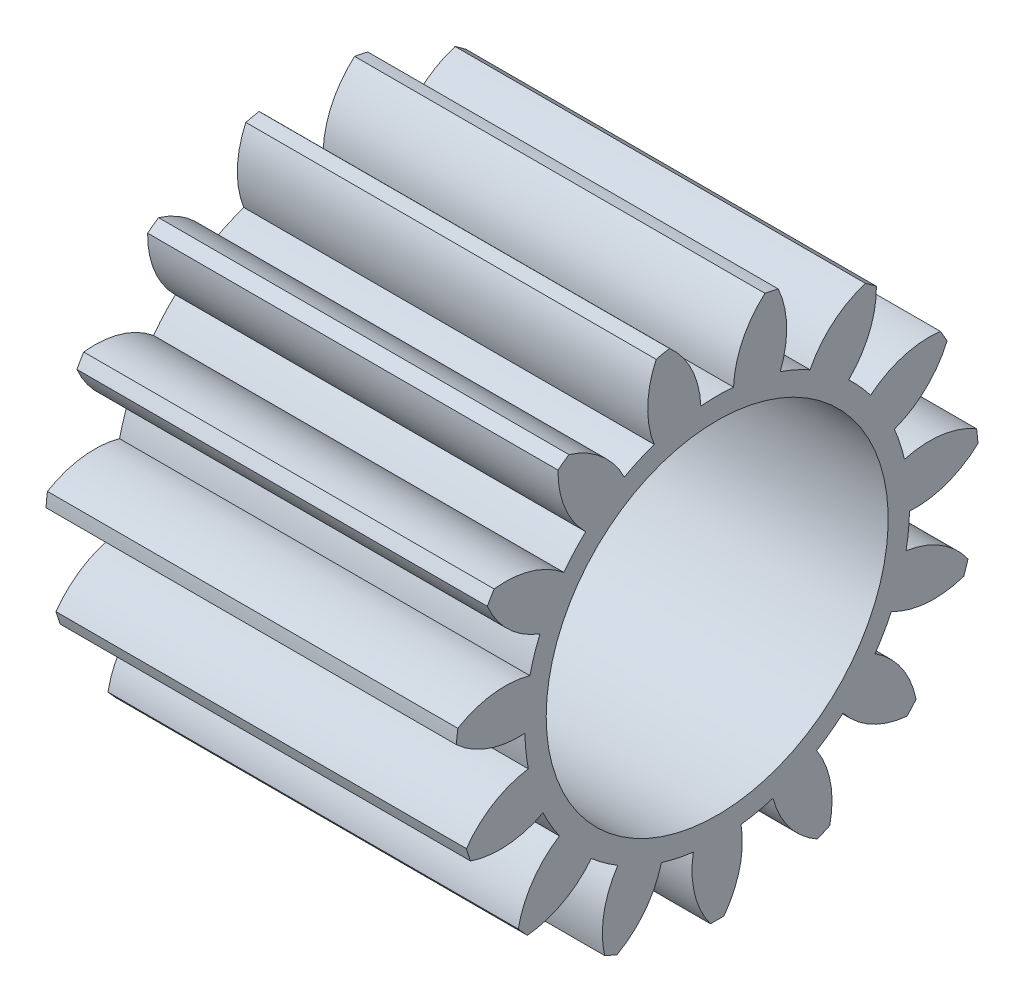
SolidWorks part; units mm, degrees
ref_plane "Plane1" through (0, 0, 0) normal (0, 0, 1) x (1, 0, 0)
ref_plane "Plane2" through (0, 0, 0) normal (0, 1, 0) x (1, 0, 0)
ref_plane "Plane3" through (0, 0, 0) normal (1, 0, 0) x (0, 0, -1)
other "Configuration Table"
sketch "HoldingSke" plane through (0, 0, 0) normal (0, 1, 0) x (1, 0, 0)
  line L0 (0, 0) -> (1.0733, -0.2876)
  line L1 (-15, 0) -> (100, 0) construction
  line L2 (0, 0) -> (-2.1039, 2.3779)
  line L3 (0, 0) -> (-11.863, 4.5341)
  line L4 (0, 0) -> (8.3417, 2.2352)
  line L5 (0, 0) -> (-46.8476, -17.4728)
  line L6 (0, 0) -> (-9.9476, -6.7116)
  line L7 (-2.1039, 2.3779) -> (8.6586, 51.2059)
  line L8 (-76.2, 54.61) -> (-74.4, 54.61)
  line L9 (-71.009, 38.7566) -> (-53.1078, 45.2721)
  line L10 (-76.2, 71.12) -> (104.1128, 71.12)
  line L11 (0, 0) -> (-12, 0)
  line L12 (-76.2, 101.6) -> (-76.166, 101.6)
  line L13 (24.9733, 27.94) -> (52.9518, 28.4284)
  line L14 (24.9733, 27.94) -> (24.9743, 27.94)
  line L15 (24.9733, 27.94) -> (100.4006, 29.5858)
  line L16 (-63.627, -0.9) -> (-12.827, -0.9)
  circle A0 centre (0, 0) radius 5
  circle A1 centre (0, 0) radius 5.624
  circle A2 centre (0, 0) radius 37.5
  circle A3 centre (0, 0) radius 5
  dimension "MHD" = 11.248
  dimension "Hub_dia" = 75
  dimension "Bore" = 10
  dimension "MBD" = 10
  dimension "Num_teeth" = 15
  dimension "Pitch" = 1.1111
  dimension "Overall_len" = 50
  dimension "Show_teeth" = 15
  dimension "Thickness" = 12
  dimension "OAL" = 50.0001
  dimension "T_dim" = 1.8
  dimension "Ap" = 20
  dimension "H" = 19.05
  dimension "Pitch_radius" = 180.3128
  dimension "Width" = 12
  dimension "Backlash" = 0.034
  dimension "Addendum_fac" = 1
  dimension "Dedendum_fac" = 1.25
  dimension "Clearance_fac" = 0.25
  dimension "Dedendum_add" = 0.001
  dimension "Module" = 0.9
sketch "BasProSke" plane through (0, 0, 0) normal (0, 1, 0) x (1, 0, 0)
  line L0 (-10, 0) -> (60, 0) construction
  line L1 (0, 0) -> (0, 7.65)
  line L2 (0, 0) -> (12, 0)
  line L3 (12, 0) -> (12, 7.65)
  line L4 (12, 7.65) -> (0, 7.65)
  dimension "Thickness" = 12
  dimension "Diameter" = 15.3
revolve "Base-Revolve" add sketch "BasProSke" angle 360 about L0
sketch "TooCutSke" plane through (0, 0, 0) normal (1, 0, 0) x (0, 0, -1)
  line L1 (0, 0) -> (0, 107) construction
  line L2 (0, 0) -> (-0.765, 6.7065) construction
  line L3 (0, 0) -> (-2.7939, 13.1444) construction
  line L4 (-0.765, 6.7065) -> (-1.397, 6.5722) construction
  arc A0 (0.4781, 5.6036) -> (-0.4781, 5.6036) centre (0, 0) ccw
  arc A1 (1.421, 7.5427) -> (-1.421, 7.5427) centre (0, 0) ccw
  circle A2 centre (0, 0) radius 6.75 construction
  circle A3 centre (0, 0) radius 6.3429 construction
  arc A4 (-0.4781, 5.6036) -> (-1.421, 7.5427) centre (-3.1758, 5.4907) ccw
  arc A5 (1.421, 7.5427) -> (0.4781, 5.6036) centre (3.1758, 5.4907) ccw
  dimension "Root_dia" = 11.248
  dimension "Overcut_dia" = 15.3508
  dimension "Pitch_dia" = 13.5
  dimension "Base_dia" = 12.6859
  dimension "Flank_rad" = 2.7
  dimension "Half_ang" = 12
  dimension "Half_CT" = 0.6461
extrude "ToothCut" cut sketch "TooCutSke" along normal through all
fillet "Breaks" [suppressed] radius 0.018
fillet "RootFillets" [suppressed] radius 0.226
pattern_circular "TeethCuts" count 15 every 24 about axis through (-10, 0, 0) along (1, 0, 0) of "ToothCut", "RootFillets", "Breaks"
sketch "HubNeaOneSke" plane through (0, 0, 0) normal (-1, 0, 0) x (0, 0, 1)
  circle A0 centre (0, 0) radius 5.624
  dimension "Diameter" = 11.248
extrude "HubNearOne" [suppressed] add sketch "HubNeaOneSke" along normal blind 38.0001
sketch "HubNeaBotSke" plane through (0, 0, 0) normal (-1, 0, 0) x (0, 0, 1)
  circle A0 centre (0, 0) radius 5.624
  dimension "Diameter" = 11.248
extrude "HubNearBoth" [suppressed] add sketch "HubNeaBotSke" along normal blind 19
ref_plane "FarPln" through (12, 0, 0) normal (1, 0, 0) x (0, 0, -1)
sketch "HubFarSke" plane through (12, 0, 0) normal (1, 0, 0) x (0, 0, -1)
  circle A0 centre (0, 0) radius 5.624
  dimension "Diameter" = 11.248
extrude "HubFar" [suppressed] add sketch "HubFarSke" along normal blind 19
sketch "BorSke" plane through (0, 0, 0) normal (1, 0, 0) x (0, 0, -1)
  circle A0 centre (0, 0) radius 5
  dimension "Diameter" = 10
extrude "Bore" cut sketch "BorSke" along normal mid plane 100.0001
sketch "KeySke" plane through (0, 0, 0) normal (1, 0, 0) x (0, 0, -1)
  line L0 (-2, 0) -> (-2, 6.8)
  line L1 (-2, 6.8) -> (2, 6.8)
  line L2 (2, 6.8) -> (2, 0)
  line L3 (0, 0) -> (0, 34) construction
  line L4 (-2, 0) -> (2, 0)
  dimension "Offset" = 6.8
  dimension "Width" = 4
extrude "Keyway" [suppressed] cut sketch "KeySke" along normal mid plane 100.0001
pattern_circular "Keyway2" [suppressed] count 2 every 90 about axis through (-10, 0, 0) along (1, 0, 0)
sketch "Sketch1" plane through (12, 0, 0) normal (1, 0, 0) x (0, 0, -1)
  circle A0 centre (0, 0) radius 6.5
  dimension "D1" = 13
sketch "Sketch2" plane through (12, 0, 0) normal (1, 0, 0) x (0, 0, -1)
  line L0 (0, 10) -> (0, -10) construction
  line L1 (-10, 0) -> (10, 0) construction
  point P5 (0, 0)
  point P6 (0, 0)
  dimension "D1" = 20
  dimension "D2" = 20
  dimension "D3" = 0
equation "' \"Module@HoldingSke\" = 6.35"
equation "' \"Num_teeth@HoldingSke\" = 12"
equation "' \"Ap@HoldingSke\" =  20"
equation "' \"Ap@HoldingSke\" = 20"
equation "' \"Width@HoldingSke\" = 0.5 * 25.4"
equation "' \"Hub_dia@HoldingSke\"= 1 * 25.4"
equation "' \"Hub_dia@HoldingSke\" = 1 * 25.4"
equation "' \"Overall_len@HoldingSke\" = 1.0 * 25.4"
equation "' \"Bore@HoldingSke\" = 0.75 * 25.4"
equation "' \"T_dim@HoldingSke\" = 0.1 * 25.4"
equation "' \"Width@KeySke\" = 0.25 * 25.4"
equation "' \"Show_teeth@HoldingSke\" = 13"
equation "' \"Backlash@HoldingSke\" = 0.009 * 25.4"
equation "' \"Addendum_fac@HoldingSke\" = 1.0"
equation "' \"Dedendum_fac@HoldingSke\" = 1.25"
equation "' \"Dedendum_add@HoldingSke\" = 0.00005 * 25.4"
equation "' \"Clearance_fac@HoldingSke\" = 0.25"
equation "\"Pitch@HoldingSke\" = 1 / \"Module@HoldingSke\""
equation "\"Overcut_dia@TooCutSke\" = (\"Num_teeth@HoldingSke\" + 2 * \"Addendum_fac@HoldingSke\") / \"Pitch@HoldingSke\" + 0.002 * 25.4"
equation "\"Pitch_dia@TooCutSke\" = \"Num_teeth@HoldingSke\" / \"Pitch@HoldingSke\""
equation "\"Base_dia@TooCutSke\" = \"Num_teeth@HoldingSke\" / \"Pitch@HoldingSke\" * cos((\"Ap@HoldingSke\"  * 3.14159265 / 180))"
equation "\"Root_dia@TooCutSke\" = (\"Num_teeth@HoldingSke\" + 2) / \"Pitch@HoldingSke\" - 2 * (\"Addendum_fac@HoldingSke\" + \"Dedendum_fac@HoldingSke\") / \"Pitch@HoldingSke\" - \"Dedendum_add@HoldingSke\" * 2"
equation "\"Half_ang@TooCutSke\" = 180 / \"Num_teeth@HoldingSke\""
equation "\"Half_CT@TooCutSke\" = \"Num_teeth@HoldingSke\" / \"Pitch@HoldingSke\" * sin((3.14159265 / 2 / \"Num_teeth@HoldingSke\")) / 2 - 7 * \"Backlash@HoldingSke\" / 4"
equation "\"Flank_rad@TooCutSke\" = \"Num_teeth@HoldingSke\" / \"Pitch@HoldingSke\" / 5"
equation "\"Radius@RootFillets\" = \"Clearance_fac@HoldingSke\" / \"Pitch@HoldingSke\" + \"Dedendum_add@HoldingSke\""
equation "\"Break_rad@Breaks\" = 0.02 / \"Pitch@HoldingSke\""
equation "\"Thickness@HoldingSke\" = \"Width@HoldingSke\""
equation "\"OAL@HoldingSke\" = \"Thickness@HoldingSke\""
equation "\"MHD@HoldingSke\" = (\"Num_teeth@HoldingSke\" + 2) / \"Pitch@HoldingSke\" - 2 * (\"Addendum_fac@HoldingSke\" + \"Dedendum_fac@HoldingSke\")  / \"Pitch@HoldingSke\" - \"Dedendum_add@HoldingSke\" * 2"
equation "\"MBD@HoldingSke\" = (\"Num_teeth@HoldingSke\" + 2) / \"Pitch@HoldingSke\" - 2 * (\"Addendum_fac@HoldingSke\" + \"Dedendum_fac@HoldingSke\")  / \"Pitch@HoldingSke\" - \"Dedendum_add@HoldingSke\" * 2 - 0.002 * 25.4"
equation "\"MHD@HoldingSke\" = ((sgn( \"MHD@HoldingSke\" - \"Hub_dia@HoldingSke\" )-1)*( \"MHD@HoldingSke\" - \"Hub_dia@HoldingSke\" ))/-2+ \"Hub_dia@HoldingSke\""
equation "\"MBD@HoldingSke\" = ((sgn( \"MBD@HoldingSke\" - \"Bore@HoldingSke\" )-1)*( \"MBD@HoldingSke\" - \"Bore@HoldingSke\" ))/-2+ \"Bore@HoldingSke\""
equation "\"OAL@HoldingSke\" = ((sgn( \"OAL@HoldingSke\" - \"Overall_len@HoldingSke\" )+1)*( \"OAL@HoldingSke\" - \"Overall_len@HoldingSke\" ))/2 + \"Overall_len@HoldingSke\" + 0.000002 * 25.4"
equation "\"Num_teeth@TeethCuts\" = int( \"Show_teeth@HoldingSke\" ) + 1"
equation "\"Num_teeth@TeethCuts\" = ((sgn( \"Num_teeth@TeethCuts\" - \"Num_teeth@HoldingSke\" )-1)*( \"Num_teeth@TeethCuts\" - \"Num_teeth@HoldingSke\" ))/-2+ \"Num_teeth@HoldingSke\""
equation "\"Num_teeth@TeethCuts\" = ((sgn( \"Num_teeth@TeethCuts\" - 2.0)+1)*( \"Num_teeth@TeethCuts\" - 2.0))/2 +2.0"
equation "\"Angle@TeethCuts\" = 360.0 / \"Num_teeth@HoldingSke\""
equation "\"Diameter@BasProSke\" = (\"Num_teeth@HoldingSke\" + 2 * \"Addendum_fac@HoldingSke\") / \"Pitch@HoldingSke\""
equation "\"Thickness@BasProSke\"  = \"Thickness@HoldingSke\""
equation "' \"Fillet_rad@BasProSke\" =  \"Thickness@HoldingSke\" * 0.05"
equation "' \"Fillet_rad@BasProSke\" = \"Thickness@HoldingSke\" * 0.05"
equation "\"MHD@HoldingSke\" = ((sgn( \"MHD@HoldingSke\" - \"Root_dia@TooCutSke\" )-1)*( \"MHD@HoldingSke\" - \"Root_dia@TooCutSke\" ))/-2+ \"Root_dia@TooCutSke\""
equation "\"Diameter@HubNeaOneSke\" = \"MHD@HoldingSke\""
equation "\"Length@HubNearOne\" = \"OAL@HoldingSke\" - \"Thickness@BasProSke\""
equation "\"Diameter@HubNeaBotSke\" = \"MHD@HoldingSke\""
equation "\"Length@HubNearBoth\" = ( \"OAL@HoldingSke\" - \"Thickness@BasProSke\" ) / 2.0"
equation "\"Thickness@FarPln\" = \"Thickness@BasProSke\""
equation "\"Diameter@HubFarSke\" = \"MHD@HoldingSke\""
equation "\"Length@HubFar\" = ( \"OAL@HoldingSke\" - \"Thickness@BasProSke\" ) / 2.0"
equation "\"Diameter@BorSke\" = \"MBD@HoldingSke\""
equation "\"D1@Bore\" = \"OAL@HoldingSke\" * 2.0"
equation "\"D1@Keyway\" = \"OAL@HoldingSke\" * 2.0"
equation "\"Offset@KeySke\" = \"T_dim@HoldingSke\" + \"MBD@HoldingSke\" / 2.0"
